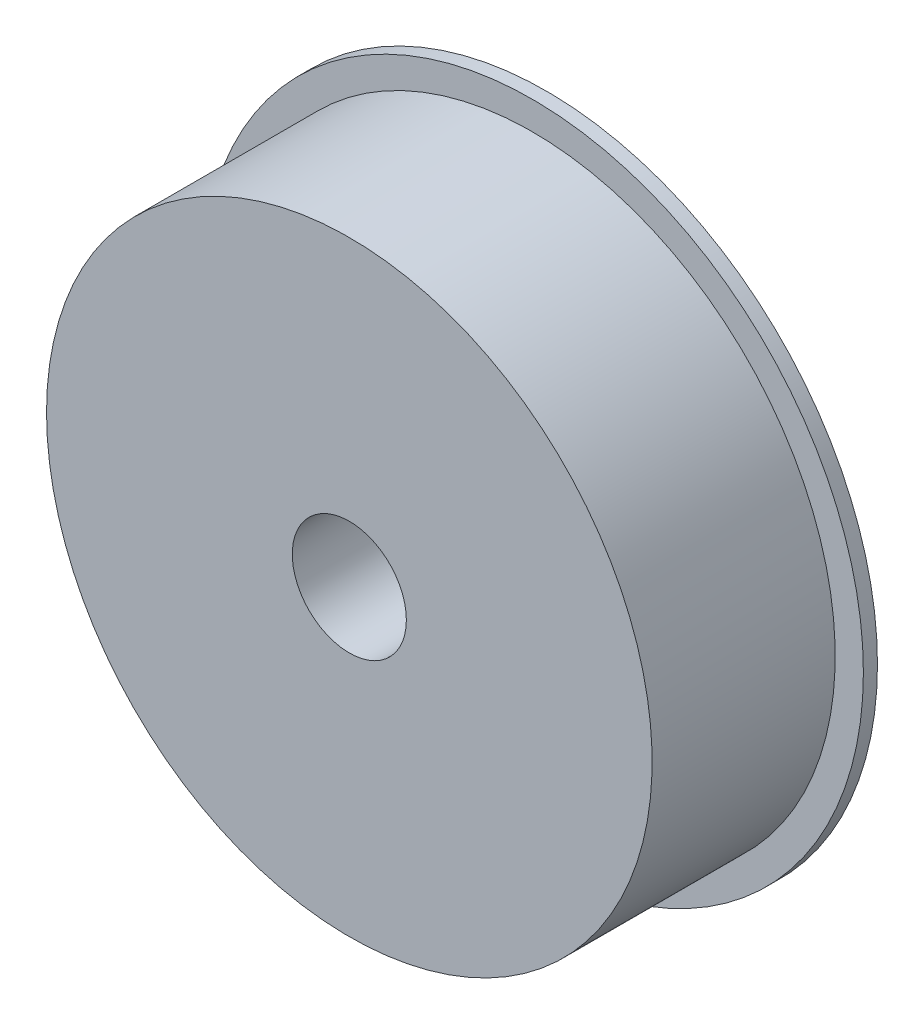
SolidWorks part; units mm, degrees
ref_plane "Alzado" through (0, 0, 0) normal (0, 0, 1) x (1, 0, 0)
ref_plane "Planta" through (0, 0, 0) normal (0, 1, 0) x (1, 0, 0)
ref_plane "Vista lateral" through (0, 0, 0) normal (1, 0, 0) x (0, 0, -1)
sketch "Croquis1" plane through (0, 0, 0) normal (0, 0, 1) x (1, 0, 0)
  circle A0 centre (0, 0) radius 23.5
  dimension "D1" = 47
extrude "Saliente-Extruir1" add sketch "Croquis1" along normal mid plane 1
sketch "Croquis2" plane through (0, 0, 0.5) normal (0, 0, 1) x (1, 0, 0)
  circle A0 centre (0, 0) radius 21.5
  dimension "D1" = 43
extrude "Saliente-Extruir2" add sketch "Croquis2" along normal blind 13
sketch "Croquis3" plane through (0, 0, 13.5) normal (0, 0, 1) x (1, 0, 0)
  circle A0 centre (0, 0) radius 4.05
  dimension "D1" = 8.1
extrude "Cortar-Extruir1" cut sketch "Croquis3" against normal blind 40
